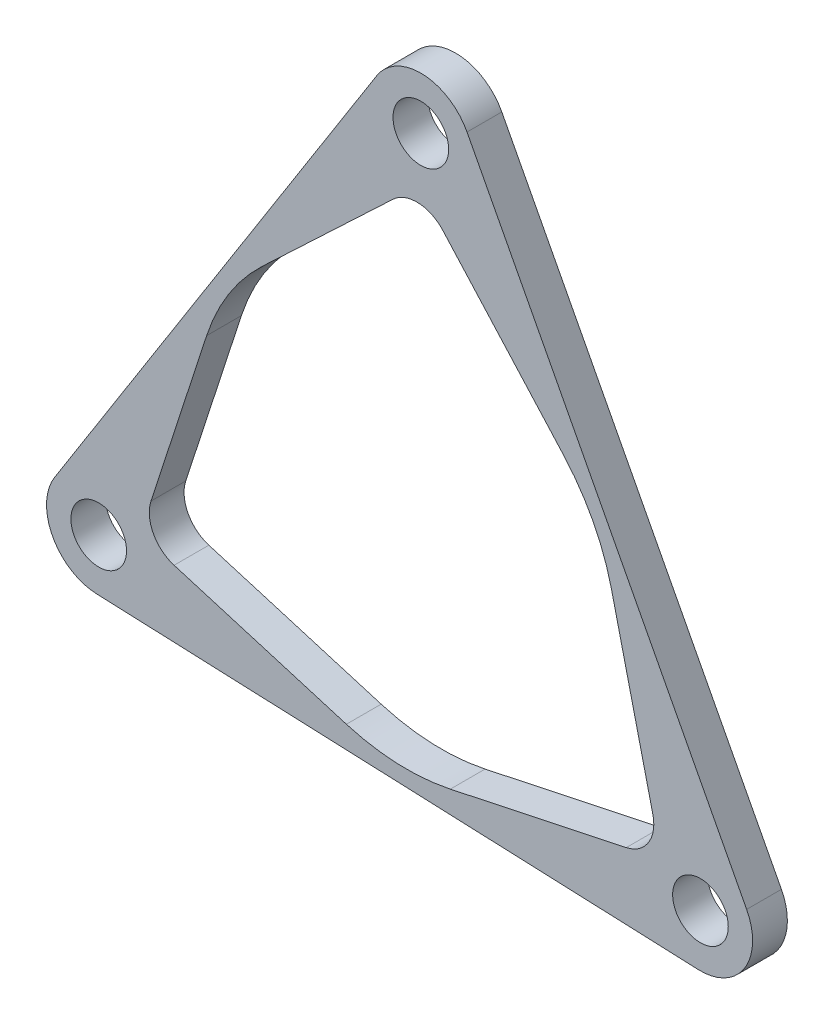
SolidWorks part; units mm, degrees
material "Thornel Mat VMA"
ref_plane "Front Plane" through (0, 0, 0) normal (0, 0, 1) x (1, 0, 0)
ref_plane "Top Plane" through (0, 0, 0) normal (0, 1, 0) x (1, 0, 0)
ref_plane "Right Plane" through (0, 0, 0) normal (1, 0, 0) x (0, 0, -1)
sketch "Sketch1" plane through (0, 0, 0) normal (0, 0, 1) x (1, 0, 0)
  line L0 (-1.7199, 21.588) -> (-20.2484, -7.6813)
  line L1 (3.4719, 21.3763) -> (19.5557, -9.3045)
  line L2 (-17.8358, -12.2835) -> (16.7764, -13.6949)
  line L3 (-0.7838, 15.8999) -> (-8.3062, 8.7987)
  line L4 (0.7057, 17.3061) -> (-15.3404, -8.0419) construction
  line L5 (-15.3404, -8.0419) -> (14.6347, -9.2642) construction
  line L6 (14.6347, -9.2642) -> (0.7057, 17.3061) construction
  line L7 (2.0759, 15.7833) -> (8.995, 8.0932)
  line L8 (-3.4668, -11.5927) -> (-13.3778, -8.6288)
  line L9 (-14.7067, -6.0939) -> (-11.5064, 3.7433)
  line L10 (11.773, 2.794) -> (14.1617, -7.2711)
  line L11 (12.6308, -9.6894) -> (2.5114, -11.8365)
  circle A0 centre (0.8149, 19.9834) radius 3
  circle A1 centre (-17.7136, -9.286) radius 3
  circle A2 centre (16.8987, -10.6974) radius 3
  circle A3 centre (0, 0) radius 12.1
  circle A4 centre (0, 0) radius 8.6603 construction
  arc A5 (2.4635, 19.9162) -> (-0.8337, 20.0506) centre (0.8149, 19.9834) ccw construction
  arc A6 (14.1617, -7.2711) -> (12.6308, -9.6894) centre (12.2157, -7.733) cw
  arc A7 (-13.3778, -8.6288) -> (-14.7067, -6.0939) centre (-12.8048, -6.7126) cw
  arc A8 (-0.7838, 15.8999) -> (2.0759, 15.7833) centre (0.5891, 14.4456) cw
  circle A9 centre (0.8149, 19.9834) radius 1.6
  circle A10 centre (-17.7136, -9.286) radius 1.6
  circle A11 centre (16.8987, -10.6974) radius 1.6
  point P35 (0, 0)
  dimension "D1" = 6
  dimension "D4" = 24.2
  dimension "D2" = 2
  dimension "D5" = 3.2
  dimension "D3" = 30
extrude "Boss-Extrude1" add sketch "Sketch1" along normal blind 2 contours A2 L1 A0 L0 A1 L2 L3 A8 L7 A3 L10 A6 L11 L8 A7 L9 | A0 A9 | A2 A11 | A1 A10
